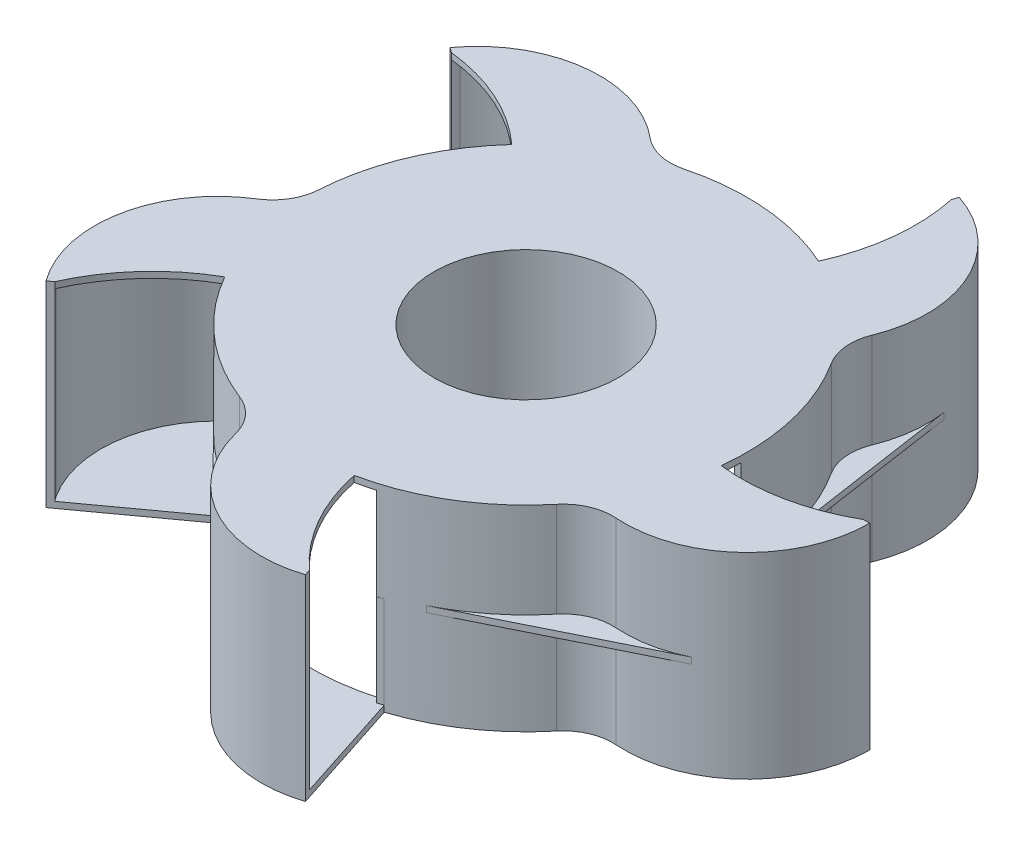
SolidWorks part; units mm, degrees
material "7075-O (SS)"
ref_plane "Front Plane" through (0, 0, 0) normal (0, 0, 1) x (1, 0, 0)
ref_plane "Top Plane" through (0, 0, 0) normal (0, 1, 0) x (1, 0, 0)
ref_plane "Right Plane" through (0, 0, 0) normal (1, 0, 0) x (0, 0, -1)
sketch "Sketch1" plane through (0, 0, 0) normal (0, 1, 0) x (1, 0, 0)
  line L0 (177.8, 0) -> (114.3, 0)
  line L1 (0, 0) -> (137.3909, -112.8564) construction
  line L2 (54.9432, -169.0978) -> (35.3206, -108.7058)
  line L3 (-143.8432, -104.5082) -> (-92.4706, -67.1839)
  line L4 (-143.8432, 104.5082) -> (-92.4706, 67.1839)
  line L5 (54.9432, 169.0978) -> (35.3206, 108.7058)
  circle A0 centre (0, 0) radius 177.8 construction
  circle A1 centre (0, 0) radius 114.3 construction
  arc A2 (177.8, 0) -> (109.7643, -63.3378) centre (114.3, 0) cw
  arc A3 (114.3, 0) -> (96.2929, 61.5805) centre (0, 0) ccw
  arc A4 (88.3227, -72.5506) -> (109.7643, -63.3378) centre (107.95, -88.6729) cw
  arc A5 (35.3206, -108.7058) -> (88.3227, -72.5506) centre (0, 0) ccw
  arc A6 (54.9432, -169.0978) -> (-26.3188, -123.9645) centre (35.3206, -108.7058) cw
  arc A7 (-41.7065, -106.4193) -> (-26.3188, -123.9645) centre (-50.9746, -130.068) cw
  arc A8 (-92.4706, -67.1839) -> (-41.7065, -106.4193) centre (0, 0) ccw
  arc A9 (-143.8432, -104.5082) -> (-126.0302, -13.2765) centre (-92.4706, -67.1839) cw
  arc A10 (-114.0987, 6.7799) -> (-126.0302, -13.2765) centre (-139.454, 8.2865) cw
  arc A11 (-92.4706, 67.1839) -> (-114.0987, 6.7799) centre (0, 0) ccw
  arc A12 (-143.8432, 104.5082) -> (-51.5721, 115.7592) centre (-92.4706, 67.1839) cw
  arc A13 (-28.8104, 110.6094) -> (-51.5721, 115.7592) centre (-35.2127, 135.1893) cw
  arc A14 (35.3206, 108.7058) -> (-28.8104, 110.6094) centre (0, 0) ccw
  arc A15 (54.9432, 169.0978) -> (94.1569, 84.8196) centre (35.3206, 108.7058) cw
  arc A16 (96.2929, 61.5805) -> (94.1569, 84.8196) centre (117.6913, 75.2651) cw
  point P38 (0, 0)
  dimension "D1" = 63.5
  dimension "D2" = 355.6
  dimension "D3" = 25.4
  dimension "D4" = 5
extrude "Boss-Extrude1" add sketch "Sketch1" along normal mid plane 101.6
sketch "Sketch3" plane through (0, 0, 0) normal (0, 1, 0) x (1, 0, 0)
  line L0 (174.5414, 0) -> (114.3, 0)
  line L1 (114.3, 0) -> (114.3, -3.175)
  line L2 (114.3, -3.175) -> (111.0796, -3.175)
  line L3 (174.5414, -3.175) -> (174.5414, 0)
  line L4 (53.9363, -165.9987) -> (35.3206, -108.7058)
  line L5 (56.9559, 165.0176) -> (53.9363, 165.9987)
  line L6 (35.3206, -108.7058) -> (32.301, -109.6869)
  line L7 (54.9432, 169.0978) -> (35.3206, 108.7058) construction
  line L8 (53.9363, 165.9987) -> (35.3206, 108.7058)
  line L9 (35.3206, 108.7058) -> (38.3402, 107.7246)
  line L10 (56.9559, 165.0176) -> (37.3451, 104.6619)
  line L11 (-139.3407, 105.1615) -> (-87.9991, 67.8596)
  line L12 (-143.0732, -100.0242) -> (-91.7315, -62.7223)
  line L13 (50.9167, -166.9799) -> (31.3059, -106.6241)
  line L14 (174.5414, -3.175) -> (111.0796, -3.175)
  line L15 (38.3402, 107.7246) -> (37.3451, 104.6619)
  line L16 (32.301, -109.6869) -> (31.3059, -106.6241)
  line L17 (50.9167, -166.9799) -> (53.9363, -165.9987)
  line L18 (-141.207, -102.5929) -> (-92.4706, -67.1839)
  line L19 (-92.4706, -67.1839) -> (-94.3369, -64.6152)
  line L20 (-94.3369, -64.6152) -> (-91.7315, -62.7223)
  line L21 (-143.0732, -100.0242) -> (-141.207, -102.5929)
  line L22 (-141.207, 102.5929) -> (-92.4706, 67.1839)
  line L23 (-92.4706, 67.1839) -> (-90.6044, 69.7525)
  line L24 (-90.6044, 69.7525) -> (-87.9991, 67.8596)
  line L25 (-139.3407, 105.1615) -> (-141.207, 102.5929)
  arc A0 (31.3059, -106.6241) -> (85.8693, -70.5353) centre (0, 0) ccw
  arc A1 (109.9911, -60.1709) -> (85.8693, -70.5353) centre (107.95, -88.6729) ccw
  arc A2 (109.9911, -60.1709) -> (174.5414, -3.175) centre (114.3, 0) ccw
  arc A3 (-91.7315, -62.7223) -> (-40.548, -103.4632) centre (0, 0) ccw
  arc A4 (-23.2368, -123.2016) -> (-40.548, -103.4632) centre (-50.9746, -130.068) ccw
  arc A5 (-23.2368, -123.2016) -> (50.9167, -166.9799) centre (35.3206, -108.7058) ccw
  arc A6 (-87.9991, 67.8596) -> (-110.9293, 6.5915) centre (0, 0) ccw
  arc A7 (-124.3522, -15.9718) -> (-110.9293, 6.5915) centre (-139.454, 8.2865) ccw
  arc A8 (-124.3522, -15.9718) -> (-143.0732, -100.0242) centre (-92.4706, -67.1839) ccw
  arc A9 (37.3451, 104.6619) -> (-28.0101, 107.537) centre (0, 0) ccw
  arc A10 (-53.6171, 113.3304) -> (-28.0101, 107.537) centre (-35.2127, 135.1893) ccw
  arc A11 (-53.6171, 113.3304) -> (-139.3407, 105.1615) centre (-92.4706, 67.1839) ccw
  circle A12 centre (0, 0) radius 50.8
  arc A30 (111.0796, -3.175) -> (93.6181, 59.87) centre (0, 0) ccw
  arc A31 (91.215, 86.0139) -> (93.6181, 59.87) centre (117.6913, 75.2651) ccw
  arc A32 (91.215, 86.0139) -> (56.9559, 165.0176) centre (35.3206, 108.7058) ccw
  arc A33 (37.3451, 104.6619) -> (-28.0101, 107.537) centre (0, 0) ccw
  arc A34 (-53.6171, 113.3304) -> (-28.0101, 107.537) centre (-35.2127, 135.1893) ccw
  arc A35 (-53.6171, 113.3304) -> (-139.3407, 105.1615) centre (-92.4706, 67.1839) ccw
  arc A36 (-87.9991, 67.8596) -> (-110.9293, 6.5915) centre (0, 0) ccw
  arc A37 (-124.3522, -15.9718) -> (-110.9293, 6.5915) centre (-139.454, 8.2865) ccw
  arc A38 (-124.3522, -15.9718) -> (-143.0732, -100.0242) centre (-92.4706, -67.1839) ccw
  arc A39 (-91.7315, -62.7223) -> (-40.548, -103.4632) centre (0, 0) ccw
  arc A40 (-23.2368, -123.2016) -> (-40.548, -103.4632) centre (-50.9746, -130.068) ccw
  arc A41 (-23.2368, -123.2016) -> (50.9167, -166.9799) centre (35.3206, -108.7058) ccw
  arc A42 (31.3059, -106.6241) -> (85.8693, -70.5353) centre (0, 0) ccw
  arc A43 (109.9911, -60.1709) -> (85.8693, -70.5353) centre (107.95, -88.6729) ccw
  arc A44 (109.9911, -60.1709) -> (174.5414, -3.175) centre (114.3, 0) ccw
  arc A45 (111.0796, -3.175) -> (93.6181, 59.87) centre (0, 0) ccw
  arc A46 (91.215, 86.0139) -> (93.6181, 59.87) centre (117.6913, 75.2651) ccw
  arc A47 (91.215, 86.0139) -> (56.9559, 165.0176) centre (35.3206, 108.7058) ccw
  point P47 (0, 0)
  dimension "D3" = 101.6
  dimension "D1" = 3.175
  dimension "D2" = 5
extrude "Cut-Extrude1" cut sketch "Sketch3" against normal offset from surface 3.175 and the other way offset from surface (47.625 mm away) 3.175 up to face at (0, -50.8, 0) other way up to face at (0, 50.8, 0)
sketch "Sketch4" plane through (0, 50.8, 0) normal (0, 1, 0) x (1, 0, 0)
  circle A0 centre (0, 0) radius 47.625
  circle A1 centre (0, 0) radius 50.8 construction
  dimension "D1" = 3.175
extrude "Cut-Extrude2" cut sketch "Sketch4" against normal through all
sketch "Sketch5" plane through (0, -50.8, 0) normal (0, -1, 0) x (-1, 0, 0)
  circle A0 centre (0, 0) radius 111.125
  circle A1 centre (0, 0) radius 50.8
  arc A2 (28.0101, 107.537) -> (-37.3451, 104.6619) centre (0, 0) ccw construction
  circle A3 centre (0, 0) radius 50.8 construction
extrude "Cut-Extrude3" cut sketch "Sketch5" against normal up to surface (50.8 mm away) up to plane "Top Plane"
sketch "Sketch6" plane through (0, 50.8, 0) normal (0, 1, 0) x (1, 0, 0)
  line L0 (114.3, 0) -> (174.5414, 0)
  line L1 (0, 0) -> (35.3206, 108.7058) construction
  line L2 (0, 0) -> (47.1624, 104.1163) construction
  line L3 (35.3206, 108.7058) -> (47.1624, 104.1163) construction
  line L4 (35.3206, 108.7058) -> (53.9363, 165.9987)
  line L5 (35.3206, -108.7058) -> (53.9363, -165.9987)
  line L6 (-92.4706, -67.1839) -> (-141.207, -102.5929)
  line L7 (-92.4706, 67.1839) -> (-141.207, 102.5929)
  arc A0 (35.3206, 108.7058) -> (47.1624, 104.1163) centre (0, 0) cw
  arc A1 (47.1624, 104.1163) -> (53.9363, 165.9987) centre (-43.9895, 145.4061) ccw
  arc A2 (114.3, 0) -> (113.5944, -12.6804) centre (0, 0) cw
  arc A3 (113.5944, -12.6804) -> (174.5414, 0) centre (124.6959, 86.7694) ccw
  arc A4 (35.3206, -108.7058) -> (23.0428, -111.9532) centre (0, 0) cw
  arc A5 (23.0428, -111.9532) -> (53.9363, -165.9987) centre (121.0558, -91.7796) ccw
  arc A6 (-92.4706, -67.1839) -> (-99.3532, -56.5105) centre (0, 0) cw
  arc A7 (-99.3532, -56.5105) -> (-141.207, -102.5929) centre (-49.8793, -143.4924) ccw
  arc A8 (-92.4706, 67.1839) -> (-84.4465, 77.0278) centre (0, 0) cw
  arc A9 (-84.4465, 77.0278) -> (-141.207, 102.5929) centre (-151.8829, 3.0965) ccw
  point P27 (0, 0)
  dimension "D1" = 12.7
  dimension "D2" = 5
extrude "Cut-Extrude4" cut sketch "Sketch6" against normal up to surface (50.8 mm away)
sketch "Sketch7" plane through (0, 0, 0) normal (0, 1, 0) x (1, 0, 0)
  line L0 (-10.0578, -153.1247) -> (-81.6813, -79.9541)
  line L1 (-148.7383, -37.7526) -> (-101.2818, 52.9763)
  line L2 (-81.8675, 129.7923) -> (19.0857, 112.6953)
  line L3 (98.1414, 117.9687) -> (113.0774, 16.6732)
  line L4 (142.5222, -56.8837) -> (50.8, -102.3907)
  arc A0 (-26.3188, -123.9645) -> (54.9432, -169.0978) centre (35.3206, -108.7058) ccw construction
  arc A1 (-92.4706, -67.1839) -> (-41.7065, -106.4193) centre (0, 0) ccw construction
  arc A2 (-26.3188, -123.9645) -> (-41.7065, -106.4193) centre (-50.9746, -130.068) ccw construction
  arc A3 (-81.6813, -79.9541) -> (-41.7065, -106.4193) centre (0, 0) ccw
  arc A4 (-26.3188, -123.9645) -> (-41.7065, -106.4193) centre (-50.9746, -130.068) ccw
  arc A5 (-26.3188, -123.9645) -> (-10.0578, -153.1247) centre (35.3206, -108.7058) ccw
  arc A6 (-126.0302, -13.2765) -> (-148.7383, -37.7526) centre (-92.4706, -67.1839) ccw
  arc A7 (-126.0302, -13.2765) -> (-114.0987, 6.7799) centre (-139.454, 8.2865) ccw
  arc A8 (-101.2818, 52.9763) -> (-114.0987, 6.7799) centre (0, 0) ccw
  arc A9 (-51.5721, 115.7592) -> (-81.8675, 129.7923) centre (-92.4706, 67.1839) ccw
  arc A10 (-51.5721, 115.7592) -> (-28.8104, 110.6094) centre (-35.2127, 135.1893) ccw
  arc A11 (19.0857, 112.6953) -> (-28.8104, 110.6094) centre (0, 0) ccw
  arc A12 (94.1569, 84.8196) -> (98.1414, 117.9687) centre (35.3206, 108.7058) ccw
  arc A13 (94.1569, 84.8196) -> (96.2929, 61.5805) centre (117.6913, 75.2651) ccw
  arc A14 (113.0774, 16.6732) -> (96.2929, 61.5805) centre (0, 0) ccw
  arc A15 (109.7643, -63.3378) -> (142.5222, -56.8837) centre (114.3, 0) ccw
  arc A16 (109.7643, -63.3378) -> (88.3227, -72.5506) centre (107.95, -88.6729) ccw
  arc A17 (50.8, -102.3907) -> (88.3227, -72.5506) centre (0, 0) ccw
  point P36 (0, 0)
  dimension "D1" = 5
extrude "Boss-Extrude2" add sketch "Sketch7" along normal mid plane 3.175
sketch "Sketch8" plane through (0, 0, 0) normal (0, 0, -1) x (-1, 0, 0)
  line L0 (0, -50.8) -> (-219.8841, -50.8) construction
  line L1 (-219.8841, -50.8) -> (-166.6408, 77.7408) construction
  line L2 (-166.6408, 77.7408) -> (-101.6, 50.8) construction
  line L4 (-219.8841, -50.8) -> (-219.8841, 0) construction
  line L5 (-219.8841, 0) -> (-219.8841, 50.8) construction
  line L6 (0, 0) -> (0, 50.8) construction
  line L9 (0, 0) -> (0, -50.8) construction
  line L13 (-219.8841, 50.8) -> (-101.6, 50.8) construction
  line L14 (-219.8841, 0) -> (0, 0) construction
  point P0 (-177.8, 50.8)
  point P2 (-167.1534, 77.2182)
  point P13 (0, 0)
  point P14 (-136.6488, 50.8)
  point P16 (-189.8608, 75.1335)
  dimension "D1" = 76.2
  dimension "D2" = 177.8
  dimension "D3" = 101.6
  dimension "D4" = 22.5
